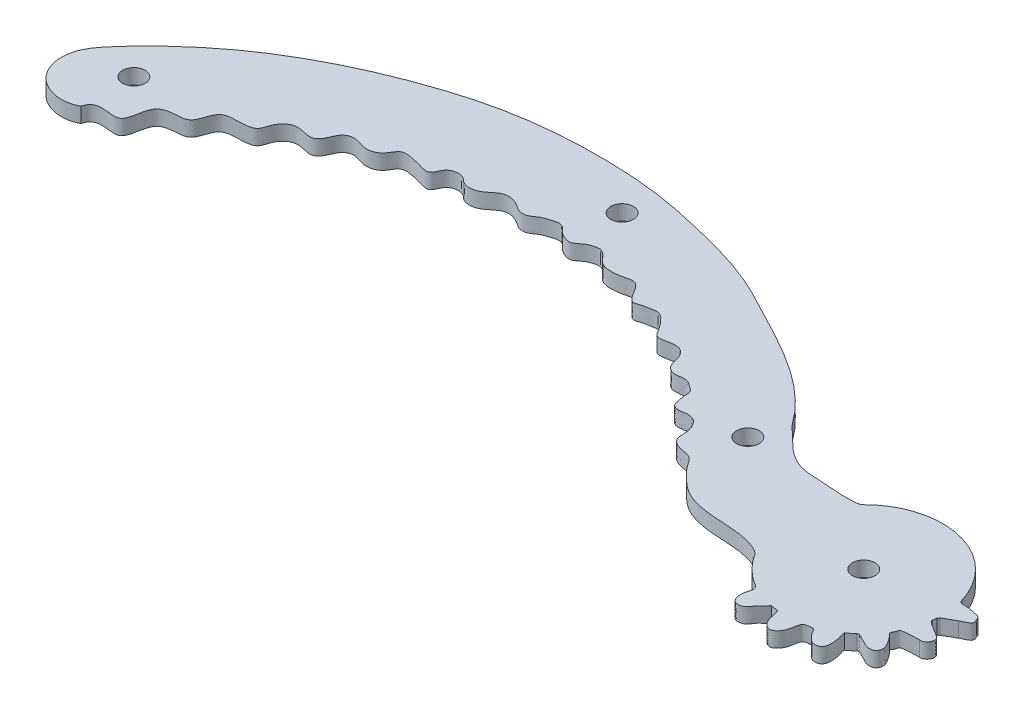
SolidWorks part; units mm, degrees
ref_plane "前视基准面" through (0, 0, 0) normal (0, 0, 1) x (1, 0, 0)
ref_plane "上视基准面" through (0, 0, 0) normal (0, 1, 0) x (1, 0, 0)
ref_plane "右视基准面" through (0, 0, 0) normal (1, 0, 0) x (0, 0, -1)
sketch "草图1" plane through (0, 0, 0) normal (0, 1, 0) x (1, 0, 0)
  line L0 (10.2272, 3.4888) -> (10.2907, 3.2997)
  line L1 (12.3874, 0.8543) -> (10.8169, -0.0438)
  circle A0 centre (0.1637, 0.4928) radius 1.5
  circle A1 centre (-22.713, 7.9815) radius 1.5
  circle A2 centre (-56.8508, 25.4199) radius 1.5
  circle A3 centre (-104.9097, 8.6589) radius 1.5
  arc A4 (-1.795, -9.8229) -> (-0.8489, -9.9582) centre (0.1637, 0.4928) ccw
  arc A5 (-8.8173, -4.947) -> (-5.1187, -8.5817) centre (0.1637, 0.4928) ccw
  arc A6 (10.2272, 3.4888) -> (-7.4423, 7.7315) centre (0.1637, 0.4928) ccw
  arc A7 (10.5754, -0.8659) -> (10.6365, -0.2626) centre (0.1637, 0.4928) ccw
  arc A8 (6.2008, -8.098) -> (7.1394, -7.3551) centre (0.1637, 0.4928) ccw
  spline S0 degree 3 poles (-0.8489, -9.9582) (-0.6326, -10.218) (-0.5111, -10.9413) (-0.303, -12.0534) (0.9028, -12.9963) (1.9525, -11.9342) (2.1493, -10.9215) (2.3289, -9.7018) (3.116, -9.7388) (3.7538, -9.575) (3.9951, -10.2816) (4.5365, -10.7569) (5.099, -11.5132) (6.3487, -11.4164) (6.6225, -10.4158) (6.5212, -9.604) (6.4429, -8.8873) (6.1248, -8.2762) (6.2008, -8.098) knots 0.637937 0.637937 0.637937 0.637937 0.650763 0.66889 0.685366 0.701512 0.718755 0.732972 0.742887 0.7482 0.757994 0.767233 0.779863 0.795449 0.807139 0.818591 0.829541 0.839848 0.839848 0.839848 0.839848
  spline S1 degree 3 poles (-5.1187, -8.5817) (-5.038, -8.6533) (-4.714, -9.0209) (-5.079, -9.9397) (-5.1559, -10.9137) (-4.7179, -12.0687) (-3.3012, -11.8564) (-2.8114, -10.7473) (-2.143, -10.3391) (-1.8316, -9.8731) (-1.795, -9.8229) knots 0.523721 0.523721 0.523721 0.523721 0.528248 0.545423 0.557119 0.571395 0.589105 0.601143 0.619944 0.622384 0.622384 0.622384 0.622384
  spline S2 degree 3 poles (-35.663, 10.7001) (-34.9431, 10.039) (-33.519, 10.9258) (-32.4724, 9.9268) (-31.7095, 9.5216) (-31.6964, 8.4676) (-31.5386, 7.6237) (-31.315, 6.6882) (-30.3129, 6.3641) (-29.3596, 6.7751) (-28.2373, 6.4067) (-27.5788, 5.4963) (-27.2885, 4.3664) (-27.4065, 3.2483) (-26.7281, 2.4909) (-25.7027, 2.0872) (-24.1477, 2.0442) (-23.5081, 0.6505) (-22.3215, -0.52) (-21.1436, -1.8137) (-18.727, -3.1108) (-15.2274, -3.5571) (-11.6545, -3.5396) (-9.3619, -4.4835) (-8.8173, -4.947) knots 0 0 0 0 0.036098 0.047993 0.058182 0.069735 0.087709 0.096698 0.107024 0.126401 0.138603 0.153227 0.171393 0.187122 0.197486 0.211172 0.233173 0.256561 0.268556 0.303732 0.328872 0.381864 0.448811 0.479781 0.479781 0.479781 0.479781
  spline S3 degree 3 poles (-47.4066, 17.7233) (-47.0543, 17.5007) (-46.346, 15.4178) (-44.9651, 16.1443) (-44.0836, 16.2329) (-43.2056, 16.5107) (-42.3834, 16.1346) (-41.7124, 15.3882) (-41.0369, 14.613) (-40.4133, 13.2875) (-38.8623, 13.7064) (-37.4028, 13.8655) (-36.197, 12.4677) (-36.3658, 11.2271) (-35.663, 10.7001) knots 0 0 0 0 0.161236 0.212348 0.265446 0.336193 0.378688 0.430637 0.526782 0.58317 0.682557 0.781271 0.853714 1 1 1 1
  spline S4 degree 3 poles (-71.211, 18.7228) (-70.565, 18.0183) (-68.6352, 18.0756) (-67.418, 19.704) (-65.8967, 19.8887) (-64.8335, 19.4253) (-63.9041, 18.689) (-62.7393, 18.7236) (-61.9174, 19.5075) (-60.8001, 19.8567) (-59.456, 20.2953) (-58.6657, 19.2135) (-57.8051, 18.7152) (-56.7262, 18.4444) (-55.9796, 19.2901) (-55.0519, 19.6746) (-53.9922, 19.9508) (-53.0406, 19.1291) (-52.2609, 18.0487) (-50.7711, 17.9092) (-49.1739, 18.1132) (-47.9256, 18.6114) (-47.4066, 17.7233) knots 0 0 0 0 0.101433 0.182304 0.213922 0.268057 0.309966 0.345938 0.38914 0.432999 0.482664 0.529097 0.56672 0.598853 0.644173 0.680167 0.715861 0.759457 0.810996 0.863338 0.916048 1 1 1 1
  spline S5 degree 3 poles (-105.0382, 1.7664) (-104.5409, 3.904) (-99.9194, 1.0734) (-100.6899, 6.683) (-97.9956, 7.1105) (-95.6156, 7.1356) (-95.5099, 10.6496) (-92.6895, 10.3884) (-90.475, 10.6945) (-90.2893, 12.6791) (-88.7242, 13.9841) (-87.2004, 13.5489) (-85.9767, 13.351) (-84.9797, 14.3168) (-84.7966, 15.6208) (-83.2792, 16.5152) (-82.0158, 15.8207) (-80.592, 15.7765) (-79.332, 16.4123) (-78.8206, 18.0189) (-77.0813, 17.8197) (-75.8962, 17.5406) (-74.0804, 16.9308) (-73.6641, 19.2315) (-71.8312, 19.2838) (-71.211, 18.7228) knots 0 0 0 0 0.100332 0.18604 0.234954 0.2703 0.337742 0.40192 0.43828 0.47683 0.523229 0.559517 0.584173 0.604077 0.648703 0.670042 0.71595 0.738313 0.768611 0.808998 0.834826 0.875875 0.9064 0.941714 1 1 1 1
  spline S6 degree 3 poles (-21.1345, 12.2809) (-24.8645, 17.5103) (-32.1679, 21.2411) (-42.1406, 26.5639) (-49.0488, 28.403) (-55.8072, 29.8828) (-61.9522, 30.4521) (-69.5327, 30.4556) (-77.0766, 29.4391) (-83.8879, 27.3772) (-91.4125, 24.5182) (-100.5401, 19.6079) (-107.7259, 13.2138) (-111.9678, 8.2225) (-112.0423, 5.0183) (-110.392, 1.5829) (-106.9924, 0.7082) (-105.0382, 1.7664) knots 0 0 0 0 0.162309 0.214041 0.297346 0.349154 0.396315 0.45953 0.548645 0.595484 0.646703 0.76082 0.864659 0.902713 0.926128 0.944547 1 1 1 1
  spline S7 degree 3 poles (-7.4423, 7.7315) (-7.8628, 7.6046) (-9.5481, 7.48) (-12.338, 7.8083) (-17.1616, 7.7605) (-19.6548, 10.9636) (-21.1345, 12.2809) knots 0.711172 0.711172 0.711172 0.711172 0.73662 0.803221 0.875531 1 1 1 1
  spline S8 degree 3 poles (10.2907, 3.2997) (10.3013, 3.2755) (10.4578, 2.9893) (11.5472, 3.0755) (12.3755, 2.8348) (13.3102, 2.6748) (13.4546, 2.1385) (13.7629, 1.5487) (12.9944, 1.1556) (12.5759, 0.9399) (12.3874, 0.8543) knots 0.147271 0.147271 0.147271 0.147271 0.148944 0.168525 0.193946 0.206657 0.215311 0.22412 0.240105 0.25237 0.25237 0.25237 0.25237
  spline S9 degree 3 poles (10.8169, -0.0438) (10.794, -0.0621) (10.724, -0.1236) (10.6678, -0.2031) (10.6365, -0.2626) knots 0 0 0 0 0.00168 0.005304 0.005304 0.005304 0.005304
  spline S10 degree 3 poles (10.5754, -0.8659) (10.5774, -0.8717) (10.6546, -1.0844) (11.3266, -1.5686) (12.1857, -1.9814) (13.4586, -2.9475) (12.559, -4.044) (12.0142, -3.9237) knots 0.016513 0.016513 0.016513 0.016513 0.016861 0.029457 0.059741 0.0769 0.107822 0.107822 0.107822 0.107822
  spline S11 degree 3 poles (12.0142, -3.9237) (11.3001, -3.9054) (10.6552, -3.9783) (9.4651, -4.0951) (9.4755, -4.68) (9.064, -5.1038) (9.6403, -5.5257) (9.9917, -6.0609) (10.4325, -6.6819) (10.673, -7.406) (10.3886, -8.1127) (9.4127, -8.3962) (8.5262, -7.8233) (7.7855, -7.5226) (7.3469, -7.2598) (7.1992, -7.3152) (7.1394, -7.3551) knots 0 0 0 0 0.026895 0.034085 0.0428 0.047153 0.055528 0.064644 0.076427 0.086731 0.095388 0.105066 0.124845 0.136056 0.140622 0.1439 0.1439 0.1439 0.1439
extrude "凸台-拉伸1" add sketch "草图1" along normal blind 2
